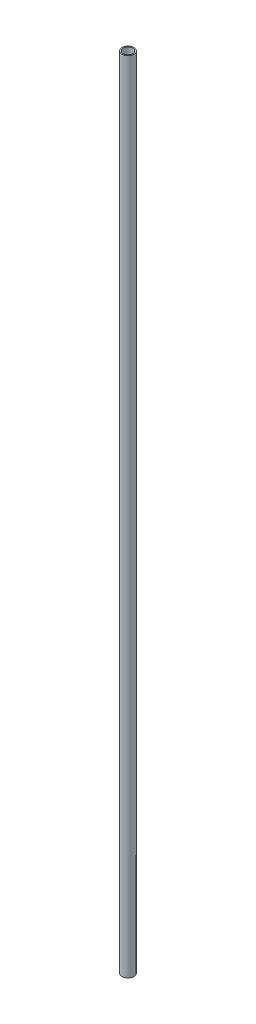
SolidWorks part; units mm, degrees
ref_plane "Front Plane" through (0, 0, 0) normal (0, 0, 1) x (1, 0, 0)
ref_plane "Top Plane" through (0, 0, 0) normal (0, 1, 0) x (1, 0, 0)
ref_plane "Right Plane" through (0, 0, 0) normal (1, 0, 0) x (0, 0, -1)
sketch "Sketch1" plane through (0, 0, 0) normal (0, 1, 0) x (1, 0, 0)
  circle A0 centre (0, 0) radius 7.5
  circle A1 centre (0, 0) radius 6
  dimension "D1" = 1.5
  dimension "D2" = 15
extrude "Boss-Extrude1" add sketch "Sketch1" along normal blind 1005
